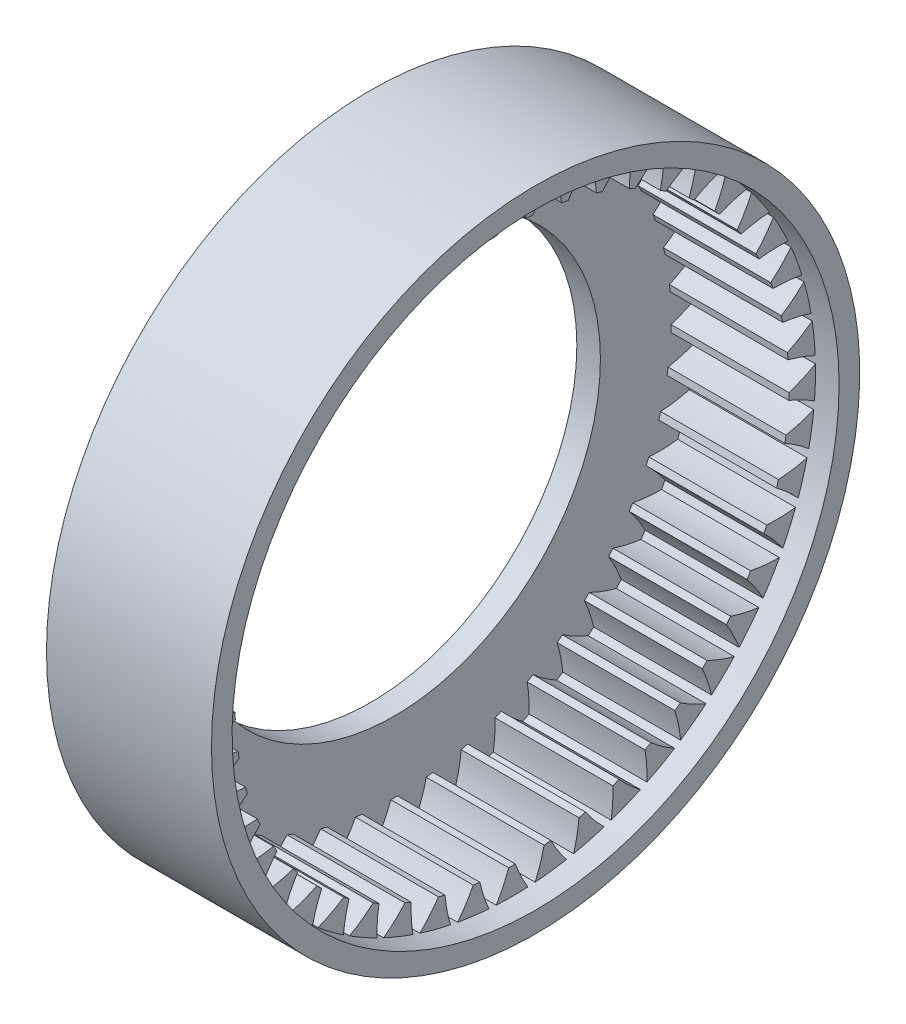
SolidWorks part; units mm, degrees
ref_plane "Plane1" through (0, 0, 0) normal (0, 0, 1) x (1, 0, 0)
ref_plane "Plane2" through (0, 0, 0) normal (0, 1, 0) x (1, 0, 0)
ref_plane "Plane3" through (0, 0, 0) normal (1, 0, 0) x (0, 0, -1)
other "Configuration Table"
sketch "HoldingSke" plane through (0, 0, 0) normal (0, 1, 0) x (1, 0, 0)
  line L0 (0, 0) -> (0.6561, -0.7547)
  line L1 (-15, 0) -> (100, 0) construction
  line L2 (0, 0) -> (-2.1039, 2.3779)
  line L3 (0, 0) -> (-11.863, 4.5341)
  line L4 (0, 0) -> (5.6657, 6.5177)
  line L5 (0, 0) -> (-23.7986, -8.8762)
  line L6 (0, 0) -> (-10.5278, -7.1032)
  line L7 (-2.1039, 2.3779) -> (3.3635, 27.1825)
  line L8 (-76.2, 3.3779) -> (-54.61, 3.3779)
  line L9 (-71.009, 38.7566) -> (-53.1078, 45.2721)
  line L10 (-76.2, 71.12) -> (104.1128, 71.12)
  line L11 (0, 0) -> (-12, 0)
  line L12 (-76.2, 101.6) -> (-76.162, 101.6)
  line L13 (24.9733, 27.94) -> (52.9518, 28.4284)
  line L14 (24.9733, 27.94) -> (24.9743, 27.94)
  line L15 (24.9733, 27.94) -> (100.4006, 29.5858)
  circle A0 centre (0, 0) radius 27.5
  circle A1 centre (0, 0) radius 12.7
  circle A2 centre (0, 0) radius 12.7
  dimension "MHD" = 25.4
  dimension "Hub_dia" = 25.4
  dimension "Diameter" = 55
  dimension "Num_teeth" = 49
  dimension "Pitch" = 1
  dimension "Overall_len" = 25.4
  dimension "Show_teeth" = 49
  dimension "Thickness" = 12.7
  dimension "OAL" = 25.4001
  dimension "T_dim" = 21.59
  dimension "Ap" = 20
  dimension "H" = 19.05
  dimension "Pitch_radius" = 180.3128
  dimension "Width" = 12
  dimension "Backlash" = 0.038
  dimension "Addendum_fac" = 1
  dimension "Dedendum_fac" = 1.25
  dimension "Clearance_fac" = 0.25
  dimension "Dedendum_add" = 0.001
  dimension "Module" = 1
sketch "BasProSke" plane through (0, 0, 0) normal (0, 1, 0) x (1, 0, 0)
  line L0 (-10, 0) -> (60, 0) construction
  line L1 (0, 23.5) -> (0, 27.5)
  line L2 (0, 23.5) -> (12, 23.5)
  line L3 (12, 23.5) -> (12, 27.5)
  line L4 (12, 27.5) -> (0, 27.5)
  dimension "Diameter" = 55
  dimension "Thickness" = 12
  dimension "Inside_diameter" = 47
revolve "Base-Revolve" add sketch "BasProSke" angle 360 about L0
sketch "TooCutSke" plane through (0, 0, 0) normal (1, 0, 0) x (0, 0, -1)
  line L3 (0.8803, 24.4842) -> (0.8803, 53.6633) construction
  line L4 (0, 0) -> (0, 59.563) construction
  line L5 (0, 0) -> (-4.3778, 68.1871) construction
  line L6 (-10.5527, 20.0854) -> (36.4375, 23.1022) construction
  circle A0 centre (0, 0) radius 24.5 construction
  circle A1 centre (0, 0) radius 25.751 construction
  circle A2 centre (0, 0) radius 20.7202 construction
  circle A3 centre (0, 0) radius 23.4746 construction
  arc A4 (1.2283, 23.4424) -> (0.3093, 25.7491) centre (-10.5527, 20.0854) ccw
  arc A5 (1.2283, 23.4424) -> (-1.2283, 23.4424) centre (0, 0) ccw
  arc A6 (0.3093, 25.7491) -> (-0.3093, 25.7491) centre (0, 0) ccw
  arc A7 (-0.3093, 25.7491) -> (-1.2283, 23.4424) centre (10.5527, 20.0854) ccw
  dimension "Pitch_dia" = 49
  dimension "Base_dia" = 41.4404
  dimension "Root_dia" = 51.502
  dimension "Overcut_dia" = 46.9492
  dimension "Flank_rad" = 12.25
  dimension "Half_ang" = 3.673
  dimension "Half_CT" = 0.8803
extrude "ToothCut" cut sketch "TooCutSke" along normal through all
fillet "Breaks" [suppressed] radius 0.1
fillet "RootFillets" [suppressed] radius 0.251
pattern_circular "TeethCuts" count 49 every 7.347 about axis through (-10, 0, 0) along (1, 0, 0) of "RootFillets", "Breaks", "ToothCut"
sketch "Sketch1" plane through (0, 0, 0) normal (-1, 0, 0) x (0, 0, 1)
  circle A0 centre (0, 0) radius 27.5
  circle A1 centre (0, 0) radius 17.5
  circle A2 centre (0, 0) radius 27.5 construction
  dimension "D1" = 10
extrude "Boss-Extrude1" add sketch "Sketch1" along normal blind 2
sketch "Sketch2" plane through (12, 0, 0) normal (1, 0, 0) x (0, 0, -1)
  circle A0 centre (0, 0) radius 25.751
extrude "Cut-Extrude1" cut sketch "Sketch2" against normal blind 2
equation "' \"Module@HoldingSke\" = 6.35"
equation "' \"Num_teeth@HoldingSke\" = 24"
equation "' \"Ap@HoldingSke\" =  14.5"
equation "' \"Ap@HoldingSke\" = 14.5"
equation "' \"Width@HoldingSke\" = 12"
equation "' \"Diameter@HoldingSke\" = 8 * 25.4"
equation "' \"Show_teeth@HoldingSke\" = 100"
equation "' \"Backlash@HoldingSke\" = 0.009 * 25.4"
equation "' \"Addendum_fac@HoldingSke\" = 1.0"
equation "' \"Dedendum_fac@HoldingSke\" = 1.25"
equation "' \"Dedendum_add@HoldingSke\" = 0.00005 * 25.4"
equation "' \"Clearance_fac@HoldingSke\" = 0.25"
equation "\"Pitch@HoldingSke\" = 1 / \"Module@HoldingSke\" "
equation "\"Overcut_dia@TooCutSke\" = (\"Num_teeth@HoldingSke\" - 2 * \"Addendum_fac@HoldingSke\") / \"Pitch@HoldingSke\" - 0.002 * 25.4"
equation "\"Pitch_dia@TooCutSke\" = \"Num_teeth@HoldingSke\" / \"Pitch@HoldingSke\""
equation "\"Base_dia@TooCutSke\" = \"Num_teeth@HoldingSke\" / \"Pitch@HoldingSke\" * cos((\"Ap@HoldingSke\"  * 3.14159265 / 180)) * 0.90"
equation "\"Root_dia@TooCutSke\" = \"Num_teeth@HoldingSke\"  / \"Pitch@HoldingSke\" + 2 *  \"Dedendum_fac@HoldingSke\"/ \"Pitch@HoldingSke\" + \"Dedendum_add@HoldingSke\" * 2"
equation "\"Half_ang@TooCutSke\" = 180 / \"Num_teeth@HoldingSke\""
equation "\"Half_CT@TooCutSke\" = \"Num_teeth@HoldingSke\" / \"Pitch@HoldingSke\" * sin((3.14159265 / 2 / \"Num_teeth@HoldingSke\")) / 2 + 10 * \"Backlash@HoldingSke\" / 4"
equation "\"Flank_rad@TooCutSke\" = \"Num_teeth@HoldingSke\" / \"Pitch@HoldingSke\" / 4"
equation "\"Radius@RootFillets\"= \"Clearance_fac@HoldingSke\" / \"Pitch@HoldingSke\" + \"Dedendum_add@HoldingSke\""
equation "\"Break_rad@Breaks\" = 0.02 / \"Pitch@HoldingSke\" * 5"
equation "\"Num_teeth@TeethCuts\" = int( \"Show_teeth@HoldingSke\" ) + 1"
equation "\"Num_teeth@TeethCuts\" = ((sgn( \"Num_teeth@TeethCuts\" - \"Num_teeth@HoldingSke\" )-1)*( \"Num_teeth@TeethCuts\" - \"Num_teeth@HoldingSke\" ))/-2+ \"Num_teeth@HoldingSke\""
equation "\"Num_teeth@TeethCuts\" = ((sgn( \"Num_teeth@TeethCuts\" - 2.0)+1)*( \"Num_teeth@TeethCuts\" - 2.0))/2 +2.0"
equation "\"Angle@TeethCuts\" = 360.0 / \"Num_teeth@HoldingSke\""
equation "\"Diameter@BasProSke\" = \"Num_teeth@HoldingSke\"  / \"Pitch@HoldingSke\" + 2 *  \"Dedendum_fac@HoldingSke\"/ \"Pitch@HoldingSke\" + \"Dedendum_add@HoldingSke\" * 2 + 0.002 * 25.4"
equation "\"Diameter@BasProSke\" = ((sgn( \"Diameter@BasProSke\"  - \"Diameter@HoldingSke\" )+1)*( \"Diameter@BasProSke\"  - \"Diameter@HoldingSke\" ))/2 + \"Diameter@HoldingSke\""
equation "\"Inside_diameter@BasProSke\" =  (\"Num_teeth@HoldingSke\" - 2 * \"Addendum_fac@HoldingSke\") / \"Pitch@HoldingSke\" "
equation "\"Thickness@BasProSke\"  = \"Width@HoldingSke\""
